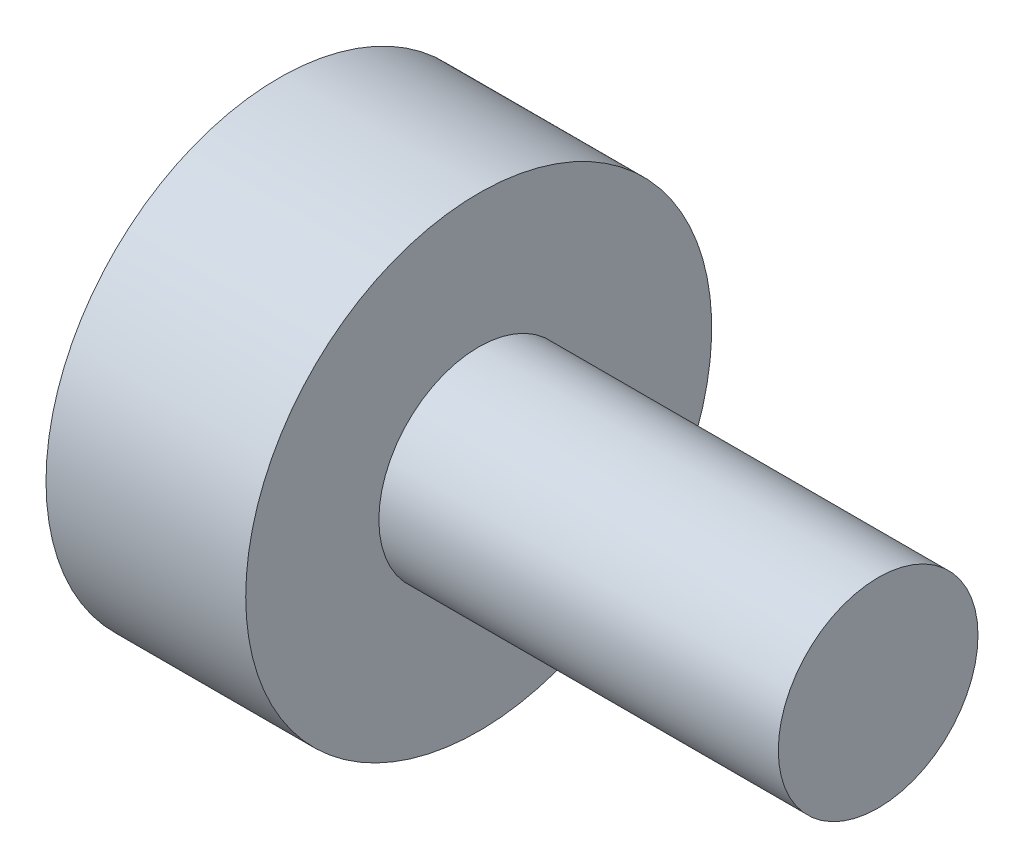
SolidWorks part; units mm, degrees
ref_plane "Спереди" through (0, 0, 0) normal (0, 0, 1) x (1, 0, 0)
ref_plane "Сверху" through (0, 0, 0) normal (0, 1, 0) x (1, 0, 0)
ref_plane "Справа" through (0, 0, 0) normal (1, 0, 0) x (0, 0, -1)
sketch "Эскиз1" plane through (0, 0, 0) normal (0, 0, 1) x (1, 0, 0)
  line L0 (0, 0) -> (100, 0)
  line L1 (0, 0) -> (0, 20)
  line L2 (0, 20) -> (10, 20)
  line L3 (10, 20) -> (10, 35)
  line L4 (10, 35) -> (40, 35)
  line L5 (40, 35) -> (40, 15)
  line L6 (40, 15) -> (100, 15)
  line L7 (100, 0) -> (100, 15)
revolve "Повернуть1" add sketch "Эскиз1" angle 360 about L0
sketch "Эскиз2" plane through (0, 0, 0) normal (1, 0, 0) x (0, 0, -1)
  circle A0 centre (0, 0) radius 5
extrude "Вырез-Вытянуть1" cut sketch "Эскиз2" along normal blind 20
